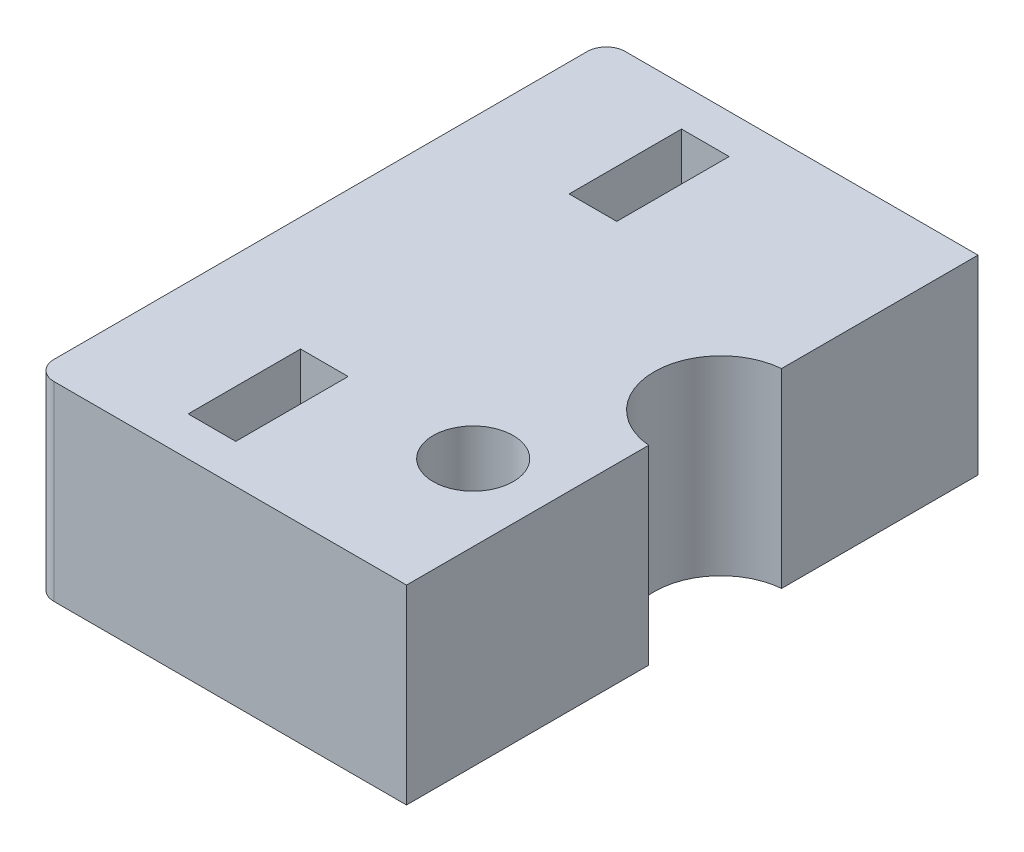
SolidWorks part; units mm, degrees
ref_plane "Front Plane" through (0, 0, 0) normal (0, 0, 1) x (1, 0, 0)
ref_plane "Top Plane" through (0, 0, 0) normal (0, 1, 0) x (1, 0, 0)
ref_plane "Right Plane" through (0, 0, 0) normal (1, 0, 0) x (0, 0, -1)
sketch "Sketch1" plane through (0, 0, 0) normal (0, 1, 0) x (1, 0, 0)
  line L1 (-29.5136, -15) -> (29.5136, -15)
  line L2 (-29.5136, -15) -> (-29.5136, 15)
  line L3 (-29.5136, 15) -> (29.5136, 15)
  line L4 (29.5136, -15) -> (29.5136, 15)
  line L5 (-29.5136, -15) -> (29.5136, 15) construction
  line L6 (-29.5136, 15) -> (29.5136, -15) construction
  point P0 (0, 0)
  dimension "D1" = 59.0272
  dimension "D2" = 30
extrude "Boss-Extrude1" add sketch "Sketch1" along normal blind 10
sketch "Sketch2" plane through (0, 10, 0) normal (0, 1, 0) x (1, 0, 0)
  line L0 (-14, -7.5) -> (6, -7.5) construction
  line L1 (-29.5136, 15) -> (-29.5136, -15) construction
  line L3 (-4, 15) -> (-4, -15) construction
  line L5 (-29.5136, -15) -> (29.5136, -15) construction
  circle A0 centre (-14, -7.5) radius 2.1
  circle A1 centre (6, -7.5) radius 2.1
  point P3 (-4, -7.5)
  point P5 (0, 0)
  point P8 (0, 0)
  dimension "D1" = 4.2
  dimension "D2" = 20
  dimension "D3" = 7.5
  dimension "D4" = 25.5136
extrude "Cut-Extrude1" cut sketch "Sketch2" against normal through all
sketch "Sketch3" plane through (29.5136, 0, 0) normal (1, 0, 0) x (0, 0, -1)
  line L0 (0, 10) -> (0, 0) construction
  line L1 (-15, 10) -> (15, 10) construction
  line L2 (-15, 0) -> (15, 0) construction
  line L3 (-10, 5) -> (10, 5) construction
  circle A0 centre (-10, 5) radius 1.65
  circle A1 centre (10, 5) radius 1.65
  point P9 (0, 5)
  dimension "D2" = 3.3
  dimension "D1" = 20
extrude "Cut-Extrude2" cut sketch "Sketch3" against normal blind 12
sketch "Sketch4" plane through (-29.5136, 0, 0) normal (-1, 0, 0) x (0, 0, 1)
  line L0 (0, 10) -> (0, 0) construction
  line L3 (-10, 5) -> (10, 5) construction
  line L4 (-15, 10) -> (15, 10) construction
  circle A0 centre (-10, 5) radius 1.7
  circle A1 centre (10, 5) radius 1.7
  point P9 (0, 5)
  dimension "D2" = 3.4
  dimension "D1" = 20
extrude "Cut-Extrude3" cut sketch "Sketch4" against normal blind 12
ref_plane "Plane1" through (23.5136, 0, 0) normal (1, 0, 0) x (0, 0, -1)
ref_plane "Plane2" through (-23.5136, 0, 0) normal (-1, 0, 0) x (0, 0, 1)
sketch "Sketch5" plane through (23.5136, 0, 0) normal (1, 0, 0) x (0, 0, -1)
  line L0 (-12.85, 6.6454) -> (-12.85, 10)
  line L1 (-7.15, 6.6454) -> (-10, 8.2909) construction
  line L2 (-10, 8.2909) -> (-12.85, 6.6454) construction
  line L3 (-12.85, 6.6454) -> (-12.85, 3.3546)
  line L4 (-12.85, 3.3546) -> (-10, 1.7091)
  line L5 (-10, 1.7091) -> (-7.15, 3.3546)
  line L6 (-7.15, 3.3546) -> (-7.15, 6.6454)
  line L7 (10, 8.2909) -> (7.15, 6.6454) construction
  line L8 (7.15, 6.6454) -> (7.15, 3.3546)
  line L9 (7.15, 3.3546) -> (10, 1.7091)
  line L10 (10, 1.7091) -> (12.85, 3.3546)
  line L11 (12.85, 3.3546) -> (12.85, 6.6454)
  line L12 (12.85, 6.6454) -> (10, 8.2909) construction
  line L13 (-15, 10) -> (15, 10) construction
  line L14 (-12.85, 10) -> (-7.15, 10)
  line L15 (-7.15, 10) -> (-7.15, 6.6454)
  line L16 (7.15, 6.6454) -> (7.15, 10)
  line L17 (7.15, 10) -> (12.85, 10)
  line L18 (12.85, 10) -> (12.85, 6.6454)
  circle A0 centre (-10, 5) radius 2.85 construction
  circle A1 centre (10, 5) radius 2.85 construction
  dimension "D1" = 5.7
extrude "Cut-Extrude4" cut sketch "Sketch5" against normal blind 2.3
sketch "Sketch6" plane through (-23.5136, 0, 0) normal (-1, 0, 0) x (0, 0, 1)
  line L0 (-12.95, 6.7032) -> (-12.95, 10)
  line L1 (-7.05, 6.7032) -> (-10, 8.4064) construction
  line L2 (-10, 8.4064) -> (-12.95, 6.7032) construction
  line L3 (-12.95, 6.7032) -> (-12.95, 3.2968)
  line L4 (-12.95, 3.2968) -> (-10, 1.5936)
  line L5 (-10, 1.5936) -> (-7.05, 3.2968)
  line L6 (-7.05, 3.2968) -> (-7.05, 6.7032)
  line L7 (10, 8.4064) -> (7.05, 6.7032) construction
  line L8 (7.05, 6.7032) -> (7.05, 3.2968)
  line L9 (7.05, 3.2968) -> (10, 1.5936)
  line L10 (10, 1.5936) -> (12.95, 3.2968)
  line L11 (12.95, 3.2968) -> (12.95, 6.7032)
  line L12 (12.95, 6.7032) -> (10, 8.4064) construction
  line L14 (-12.95, 10) -> (-7.05, 10)
  line L15 (-7.05, 10) -> (-7.05, 6.7032)
  line L16 (7.05, 6.7032) -> (7.05, 10)
  line L17 (7.05, 10) -> (12.95, 10)
  line L18 (12.95, 10) -> (12.95, 6.7032)
  line L19 (-15, 10) -> (15, 10) construction
  circle A0 centre (-10, 5) radius 2.95 construction
  circle A1 centre (10, 5) radius 2.95 construction
  circle A2 centre (-10, 5) radius 1.7 construction
  circle A3 centre (-10, 5) radius 1.7 construction
  circle A5 centre (10, 5) radius 1.7 construction
  circle A6 centre (10, 5) radius 1.7 construction
  dimension "D1" = 5.9
extrude "Cut-Extrude5" cut sketch "Sketch6" against normal blind 2.5
sketch "Sketch7" plane through (0, 10, 0) normal (0, 1, 0) x (1, 0, 0)
  line L0 (29.5136, -15) -> (29.5136, 15) construction
  line L1 (-29.5136, -15) -> (29.5136, -15) construction
  line L2 (15.7, 1.2) -> (-9.7, 1.2) construction
  circle A0 centre (15.7, 1.2) radius 3.5
  circle A1 centre (-9.7, 1.2) radius 3.5
  dimension "D3" = 7
  dimension "D1" = 13.8136
  dimension "D2" = 16.2
  dimension "D4" = 25.4
extrude "Cut-Extrude6" cut sketch "Sketch7" against normal through all
fillet "Fillet1" radius 1 4 edges at (-29.5136, 5, 15) (-29.5136, 5, -15) (29.5136, 5, -15) (29.5136, 5, 15)
sketch "Sketch8" plane through (0, 10, 0) normal (0, 1, 0) x (1, 0, 0)
  line L0 (-10, 15) -> (-10, -15)
  line L1 (28.5136, 15) -> (-28.5136, 15) construction
  line L2 (-28.5136, -15) -> (28.5136, -15) construction
  line L3 (-10, -15) -> (29.5136, -15)
  line L4 (29.5136, -15) -> (29.5136, 15)
  line L5 (29.5136, 15) -> (-10, 15)
  line L6 (29.5136, -14) -> (29.5136, 14) construction
  dimension "D1" = 10
extrude "Cut-Extrude7" cut sketch "Sketch8" against normal through all
